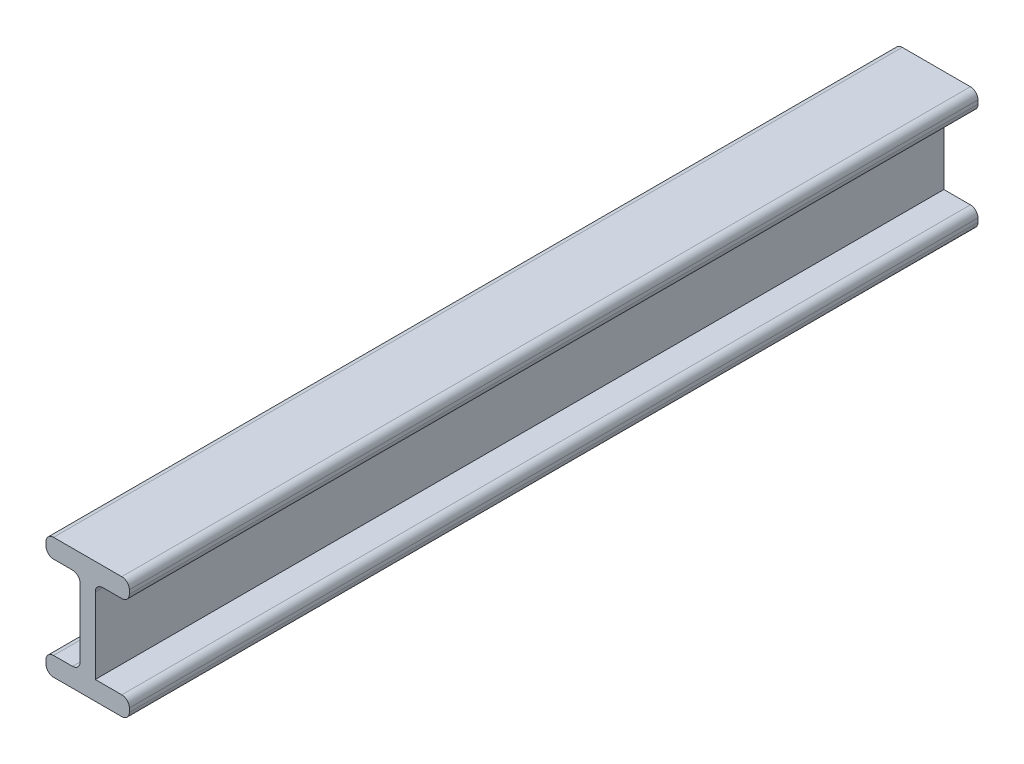
SolidWorks part; units mm, degrees
material "1060 Alloy"
ref_plane "Front Plane" through (0, 0, 0) normal (0, 0, 1) x (1, 0, 0)
ref_plane "Top Plane" through (0, 0, 0) normal (0, 1, 0) x (1, 0, 0)
ref_plane "Right Plane" through (0, 0, 0) normal (1, 0, 0) x (0, 0, -1)
sketch "Sketch1" plane through (0, 0, 0) normal (0, 0, 1) x (1, 0, 0)
  line L0 (0, -1047.7502) -> (0, -80) construction
  line L1 (-215.8369, 0) -> (207.5582, 0) construction
  line L3 (-45, 80) -> (45, 80)
  line L5 (-45, 55) -> (-20, 55)
  line L6 (55, 70) -> (55, 65)
  line L8 (10, 45) -> (10, -55)
  line L11 (55, -70) -> (55, -65)
  line L12 (-45, -55) -> (-20, -55)
  line L13 (-45, -80) -> (45, -80)
  line L14 (-55, -70) -> (-55, -65)
  line L15 (-10, 45) -> (-10, -45)
  line L16 (-55, 70) -> (-55, 65)
  line L17 (20, 55) -> (45, 55)
  line L18 (0, 80) -> (0, 91.5089) construction
  line L20 (10, -55) -> (45, -55)
  arc A0 (20, 55) -> (10, 45) centre (20, 45) ccw
  arc A1 (-10, 45) -> (-20, 55) centre (-20, 45) ccw
  arc A2 (-10, -45) -> (-20, -55) centre (-20, -45) cw
  arc A3 (-55, -65) -> (-45, -55) centre (-45, -65) cw
  arc A4 (-55, -70) -> (-45, -80) centre (-45, -70) ccw
  arc A5 (55, -70) -> (45, -80) centre (45, -70) cw
  arc A6 (55, -65) -> (45, -55) centre (45, -65) ccw
  arc A7 (45, 80) -> (55, 70) centre (45, 70) cw
  arc A8 (45, 55) -> (55, 65) centre (45, 65) ccw
  arc A9 (-55, 65) -> (-45, 55) centre (-45, 65) ccw
  arc A10 (-55, 70) -> (-45, 80) centre (-45, 70) cw
  point P12 (81.3084, 47.1589)
  point P24 (10, 55)
  point P27 (-10, 55)
  point P30 (-10, -55)
  point P33 (-55, -55)
  point P36 (-55, -80)
  point P39 (55, -80)
  point P42 (55, -55)
  point P45 (55, 80)
  point P48 (55, 55)
  point P51 (-55, 55)
  point P54 (-55, 80)
  dimension "D1" = 10
  dimension "D2" = 90
  dimension "D3" = 80
  dimension "D4" = 25
  dimension "20" = 20
extrude "Boss-Extrude1" add sketch "Sketch1" along normal blind 1120
